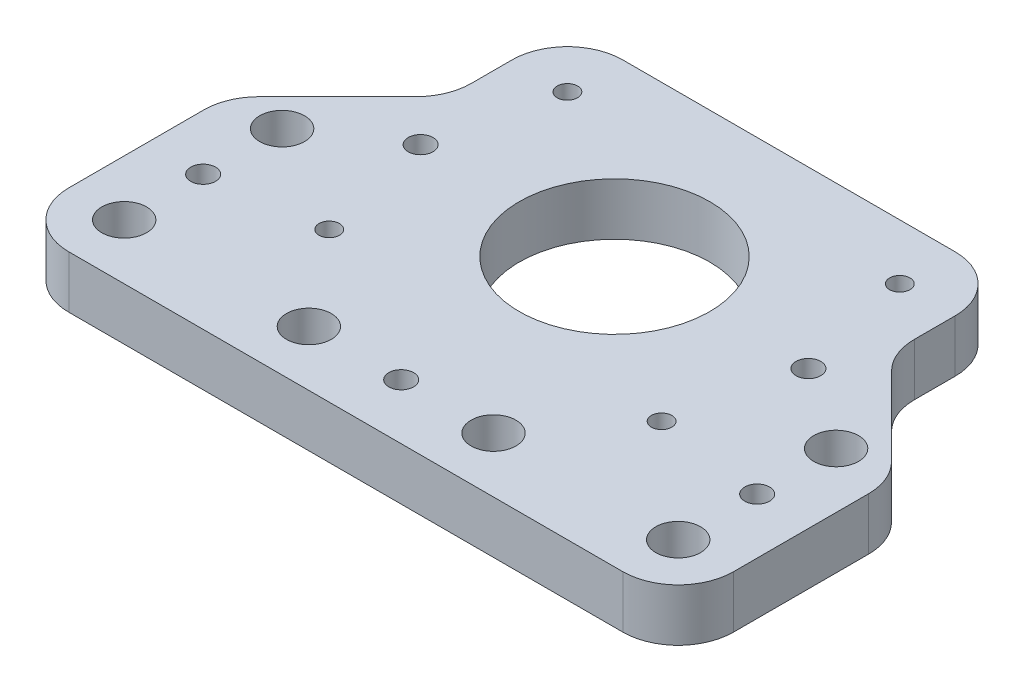
SolidWorks part; units mm, degrees
material "Balsa"
ref_plane "Front" through (0, 0, 0) normal (0, 0, 1) x (1, 0, 0)
ref_plane "Top" through (0, 0, 0) normal (0, 1, 0) x (1, 0, 0)
ref_plane "Right" through (0, 0, 0) normal (1, 0, 0) x (0, 0, -1)
sketch "Sketch1" plane through (0, 0, 0) normal (0, 1, 0) x (1, 0, 0)
  line L0 (38.1, 0) -> (38.1, 200) construction
  line L1 (0, 0) -> (76.2, 0)
  line L2 (0, 0) -> (0, 50.8)
  line L3 (0, 50.8) -> (38.1, 50.8)
  line L4 (38.1, 50.8) -> (76.2, 50.8)
  line L5 (38.1, 38.65) -> (79.051, 38.65) construction
  line L6 (38.1, 37.15) -> (79.051, 37.15) construction
  line L7 (76.2, 50.8) -> (76.2, 0)
  circle A0 centre (38.1, 118.65) radius 80 construction
  circle A1 centre (38.1, 30.8) radius 6.35 construction
  circle A2 centre (38.1, 30.8) radius 20 construction
  circle A4 centre (38.1, 30.8) radius 11
  dimension "D3" = 160
  dimension "D4" = 12.7
  dimension "D5" = 50.8
  dimension "D8" = 22
  dimension "D2" = 40
  dimension "D1" = 1.5
  dimension "D6" = 76.2
extrude "Boss-Extrude1" add sketch "Sketch1" along normal blind 6
sketch "Sketch2" plane through (0, 6, 0) normal (0, 1, 0) x (1, 0, 0)
  line L0 (38.1, 50.8) -> (38.1, 0) construction
  line L2 (0, 30.8) -> (76.2, 30.8) construction
  line L5 (76.2, 0) -> (76.2, 50.8) construction
  line L6 (76.2, 50.8) -> (0, 50.8) construction
  line L8 (0, 0) -> (76.2, 0) construction
  line L9 (0, 50.8) -> (0, 0) construction
  circle A1 centre (15.875, 30.8) radius 1.5
  circle A4 centre (60.325, 30.8) radius 1.5
  point P26 (38.1, 30.8)
  dimension "D1" = 3
  dimension "D2" = 22.225
extrude "Cut-Extrude1" cut sketch "Sketch2" against normal through all
sketch "Sketch14" plane through (0, 0, 0) normal (0, -1, 0) x (1, 0, 0)
  line L0 (38.1, -30.8) -> (3.391, -30.8) construction
  line L2 (38.1, -30.8) -> (38.1, -33.65) construction
  line L3 (19.05, -17.15) -> (57.15, -17.15) construction
  line L5 (57.15, -44.45) -> (19.05, -44.45) construction
  line L7 (76.2, -50.8) -> (0, -50.8) construction
  line L8 (60.325, -30.8) -> (38.1, -30.8) construction
  circle A0 centre (38.1, -30.8) radius 11 construction
  circle A1 centre (57.15, -44.45) radius 1.25
  circle A2 centre (19.05, -44.45) radius 1.25
  circle A3 centre (19.05, -17.15) radius 1.25
  circle A4 centre (57.15, -17.15) radius 1.25
  circle A5 centre (60.325, -30.8) radius 1.5 construction
  point P0 (57.15, -44.45)
  point P12 (19.05, -44.45)
  point P13 (19.05, -17.15)
  point P14 (57.15, -17.15)
  dimension "D3" = 2.5
  dimension "D1" = 19.05
  dimension "D2" = 6.35
extrude "M3-tap" cut sketch "Sketch14" against normal through all
sketch "Sketch15" plane through (0, 0, 0) normal (0, -1, 0) x (1, 0, 0)
  line L0 (38.1, 0) -> (38.1, -48.7422) construction
  line L2 (76.2, 0) -> (76.2, -50.8) construction
  line L3 (0, 0) -> (76.2, 0) construction
  line L5 (76.2, -24.45) -> (69.85, -24.45) construction
  line L10 (69.85, -24.45) -> (69.85, 0) construction
  line L14 (69.85, -6.35) -> (48.6833, -6.35) construction
  line L15 (48.6833, -6.35) -> (27.5167, -6.35) construction
  line L16 (27.5167, -6.35) -> (6.35, -6.35) construction
  circle A0 centre (69.85, -24.45) radius 2.65
  circle A1 centre (69.85, -6.35) radius 2.65
  circle A2 centre (48.6833, -6.35) radius 2.65
  circle A3 centre (27.5167, -6.35) radius 2.65
  circle A4 centre (6.35, -6.35) radius 2.65
  circle A5 centre (6.35, -24.45) radius 2.65
  point P0 (69.85, -24.45)
  point P1 (69.85, -6.35)
  point P35 (6.35, -6.35)
  point P36 (6.35, -24.45)
  point P42 (48.6833, -6.35)
  point P50 (27.5167, -6.35)
  dimension "D4" = 5.3
  dimension "D1" = 6.35
  dimension "D2" = 6.35
  dimension "D3" = 24.45
extrude "M5-through" cut sketch "Sketch15" against normal through all
sketch "Sketch12" plane through (0, 6, 0) normal (0, 1, 0) x (1, 0, 0)
  line L1 (0, 50.8) -> (12.7, 50.8)
  line L2 (0, 50.8) -> (0, 24.45)
  line L4 (12.7, 50.8) -> (12.7, 37.15)
  line L5 (38.1, 30.8) -> (38.1, 50.8) construction
  line L6 (76.2, 50.8) -> (0, 50.8) construction
  line L7 (63.5, 50.8) -> (63.5, 37.15)
  line L8 (76.2, 24.45) -> (63.5, 37.15)
  line L9 (76.2, 50.8) -> (76.2, 24.45)
  line L10 (76.2, 50.8) -> (63.5, 50.8)
  line L11 (12.7, 37.15) -> (0, 24.45)
  line L12 (0, 50.8) -> (0, 0) construction
  circle A1 centre (19.05, 44.45) radius 1.25 construction
  dimension "D1" = 6.35
  dimension "D2" = 13.65
  dimension "D3" = 45
extrude "Cut-Extrude2" cut sketch "Sketch12" against normal through all
fillet "Fillet2" radius 6.35 8 edges at (76.2, 3, 0) (0, 3, 0) (76.2, 3, -24.45) (63.5, 3, -37.15) (63.5, 3, -50.8) (12.7, 3, -50.8) (0, 3, -24.45) (12.7, 3, -37.15)
sketch "Sketch13" plane through (0, 0, 0) normal (0, -1, 0) x (1, 0, 0)
  line L0 (69.85, -24.45) -> (69.85, -6.35) construction
  line L1 (69.85, -6.35) -> (6.35, -6.35) construction
  line L2 (6.35, -6.35) -> (6.35, -24.45) construction
  circle A0 centre (69.85, -15.4) radius 1.5
  circle A1 centre (38.1, -6.35) radius 1.5
  circle A2 centre (6.35, -15.4) radius 1.5
  dimension "D1" = 3
extrude "Cut-Extrude3" cut sketch "Sketch13" against normal through all
other "Move Face1" face at (38.1, 6, -19.8) face at (15.875, 0, -29.3) face at (60.325, 0, -32.3) face at (57.15, 6, -45.7) face at (19.05, 6, -45.7) face at (19.05, 6, -18.4) face at (57.15, 6, -18.4) face at (69.85, 6, -27.1) face at (69.85, 6, -9) face at (48.6833, 6, -9) face at (27.5167, 6, -9) face at (6.35, 6, -9) face at (6.35, 6, -27.1) face at (69.85, 6, -16.9) face at (38.1, 6, -7.85) face at (6.35, 6, -16.9) parameters "D1"=0.08
